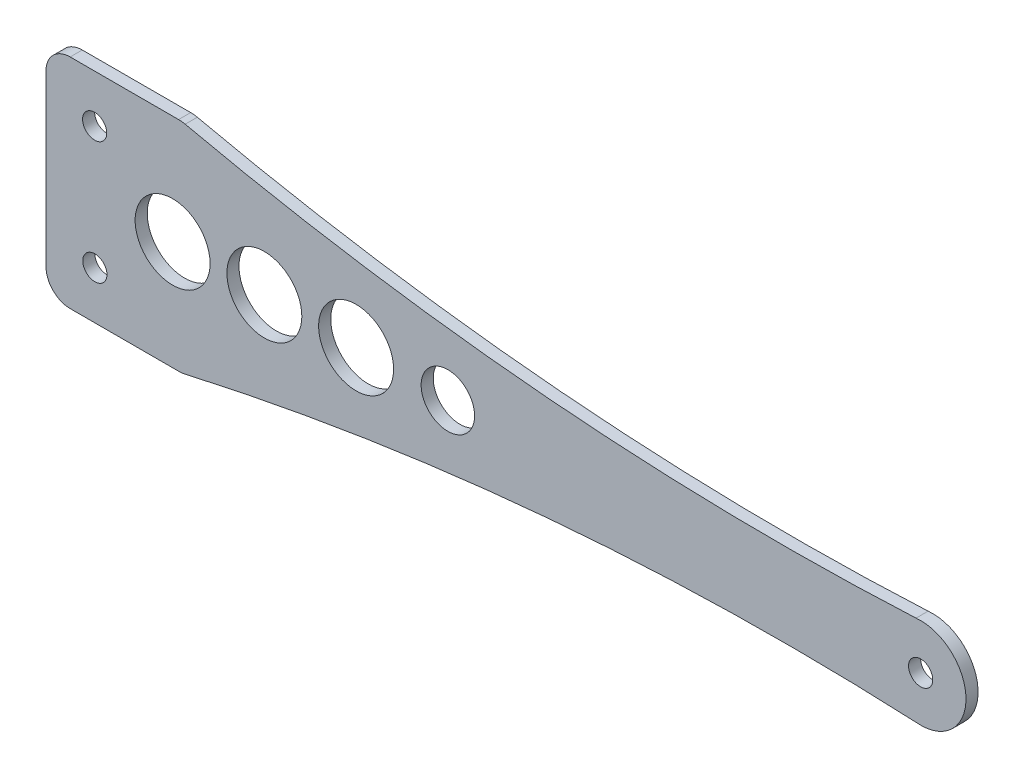
SolidWorks part; units mm, degrees
ref_plane "Alzado" through (0, 0, 0) normal (0, 0, 1) x (1, 0, 0)
ref_plane "Planta" through (0, 0, 0) normal (0, 1, 0) x (1, 0, 0)
ref_plane "Vista lateral" through (0, 0, 0) normal (1, 0, 0) x (0, 0, -1)
sketch "Croquis1" plane through (0, 0, 0) normal (0, 0, 1) x (1, 0, 0)
  line L0 (2268.2779, 1595.1617) -> (2286.2096, 1595.1617)
  line L1 (2268.2779, 1559.1129) -> (2286.1821, 1559.1129)
  line L2 (2264.2779, 1591.1617) -> (2264.2779, 1563.1129)
  arc A0 (2264.2779, 1563.1129) -> (2268.2779, 1559.1129) centre (2268.2779, 1563.1129) ccw
  circle A1 centre (2272.3255, 1587.2652) radius 2
  circle A2 centre (2408.9442, 1577.2724) radius 2
  arc A3 (2408.1984, 1569.8095) -> (2408.1828, 1584.7336) centre (2408.9442, 1577.2724) ccw
  arc A4 (2268.2779, 1595.1617) -> (2264.2779, 1591.1617) centre (2268.2779, 1591.1617) ccw
  circle A5 centre (2272.3605, 1567.0097) radius 2
  arc A6 (2287.3014, 1595.0411) -> (2408.1828, 1584.7336) centre (2385.666, 2034.6434) ccw
  arc A7 (2287.3014, 1595.0411) -> (2286.2096, 1595.1617) centre (2286.2096, 1590.1617) ccw
  arc A8 (2408.1984, 1569.8095) -> (2287.2848, 1559.236) centre (2386.6266, 1119.8535) ccw
  arc A9 (2286.1821, 1559.1129) -> (2287.2848, 1559.236) centre (2286.1821, 1564.1129) ccw
  circle A10 centre (2285.219, 1577.1425) radius 6.1983
  circle A11 centre (2300.3945, 1577.1584) radius 6.1983
  circle A12 centre (2315.5701, 1577.1743) radius 6.1983
  circle A13 centre (2330.7456, 1577.1903) radius 4.4197
extrude "Saliente-Extruir1" add sketch "Croquis1" along normal blind 2
